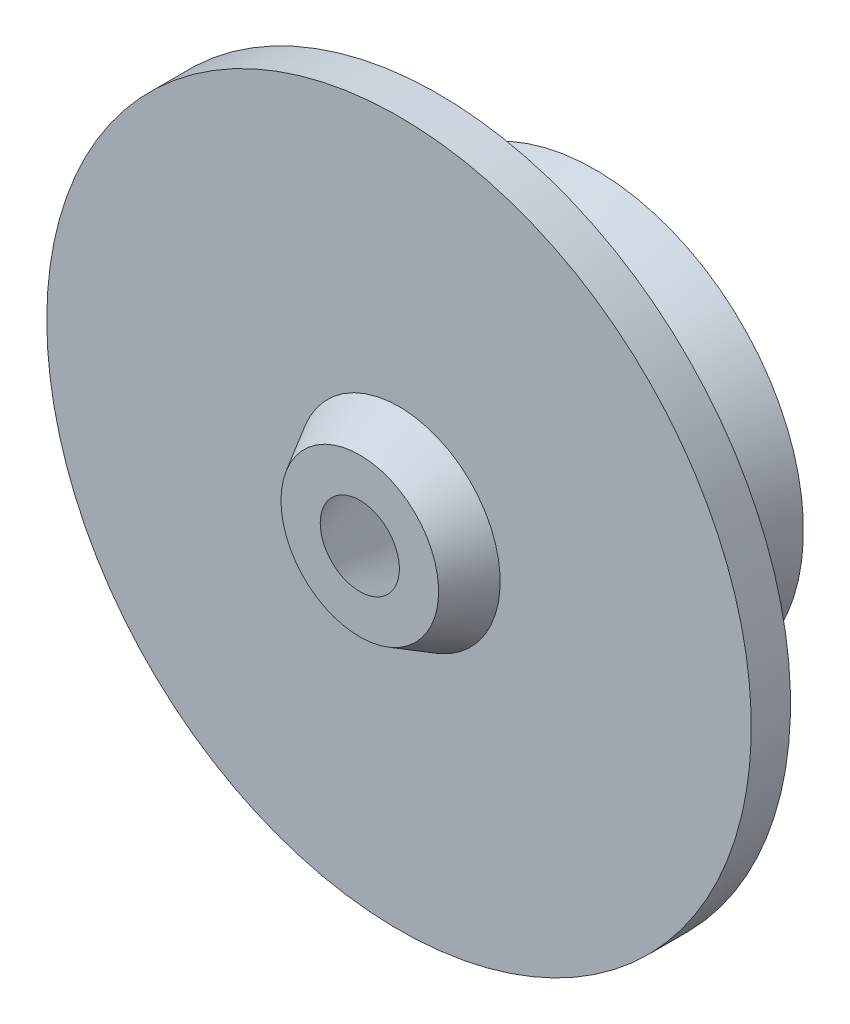
SolidWorks part; units mm, degrees
ref_plane "Front Plane" through (0, 0, 0) normal (0, 0, 1) x (1, 0, 0)
ref_plane "Top Plane" through (0, 0, 0) normal (0, 1, 0) x (1, 0, 0)
ref_plane "Right Plane" through (0, 0, 0) normal (1, 0, 0) x (0, 0, -1)
sketch "Sketch1" plane through (0, 0, 0) normal (0, 1, 0) x (1, 0, 0)
  line L0 (0, 42.5976) -> (0, -54.0834) construction
  line L1 (-6.4022, -5.6037) -> (-24.1685, 32.4963)
  line L2 (-24.1685, 32.4963) -> (-33.6935, 32.4963)
  line L3 (-33.6935, 32.4963) -> (-21.8493, 7.0963)
  line L4 (-21.8493, 7.0963) -> (-57.0034, 7.0963)
  line L5 (-57.0034, 7.0963) -> (-57.0034, 0.7463)
  line L6 (-57.0034, 0.7463) -> (-16.3697, 0.7463)
  line L7 (-16.3697, 0.7463) -> (-12.7522, -5.6037)
  line L8 (-12.7522, -5.6037) -> (-6.4022, -5.6037)
  dimension "D1" = 9.525
  dimension "D2" = 6.35
  dimension "D3" = 6.35
  dimension "D4" = 6.35
  dimension "D5" = 25
  dimension "D6" = 6.35
  dimension "D7" = 38.1
revolve "Revolve1" add sketch "Sketch1" angle 360 mid plane about L0
fillet "Fillet1" radius 12.7 1 edges at (-21.8493, 0, -7.0963)
